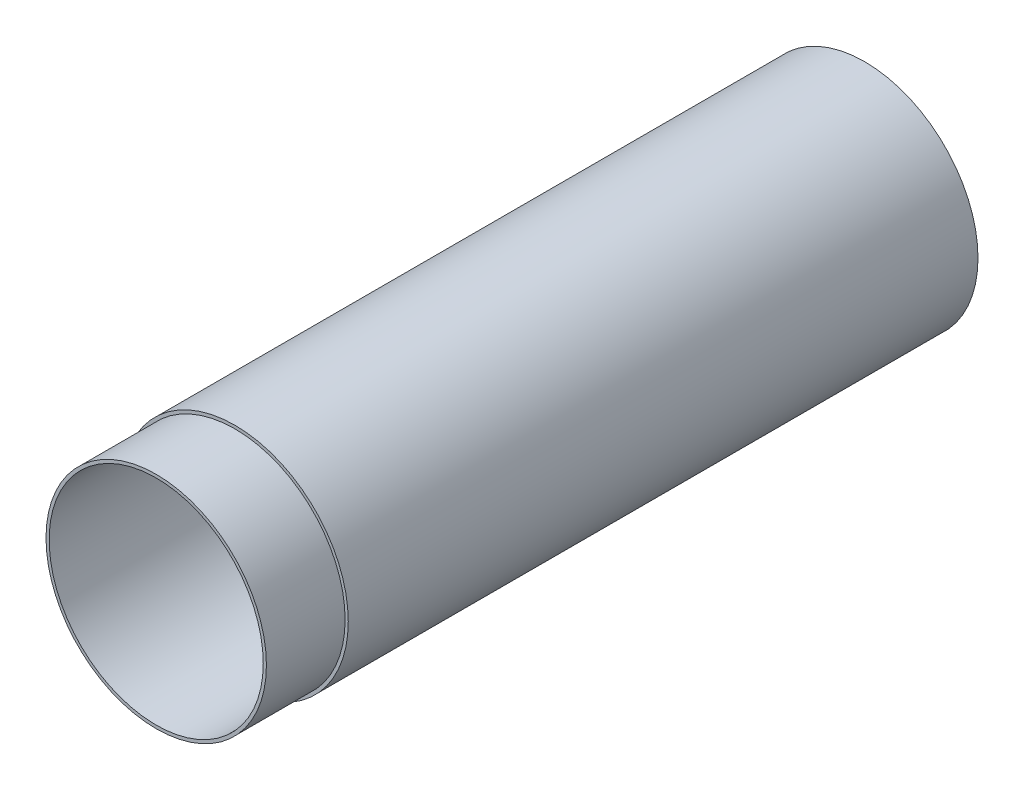
SolidWorks part; units mm, degrees
ref_plane "Plan de face" through (0, 0, 0) normal (0, 0, 1) x (1, 0, 0)
ref_plane "Plan de dessus" through (0, 0, 0) normal (0, 1, 0) x (1, 0, 0)
ref_plane "Plan de droite" through (0, 0, 0) normal (1, 0, 0) x (0, 0, -1)
sketch "Esquisse1" plane through (0, 0, 0) normal (0, 0, 1) x (1, 0, 0)
  circle A0 centre (0, 0) radius 34
  circle A1 centre (0, 0) radius 36
  point P3 (0, 0)
extrude "Boss.-Extru.1" add sketch "Esquisse1" along normal blind 225
sketch "Esquisse2" plane through (0, 0, 225) normal (0, 0, 1) x (1, 0, 0)
  circle A0 centre (0, 0) radius 35
  circle A1 centre (0, 0) radius 36
extrude "Enlèv. mat.-Extru.1" cut sketch "Esquisse2" against normal blind 25
